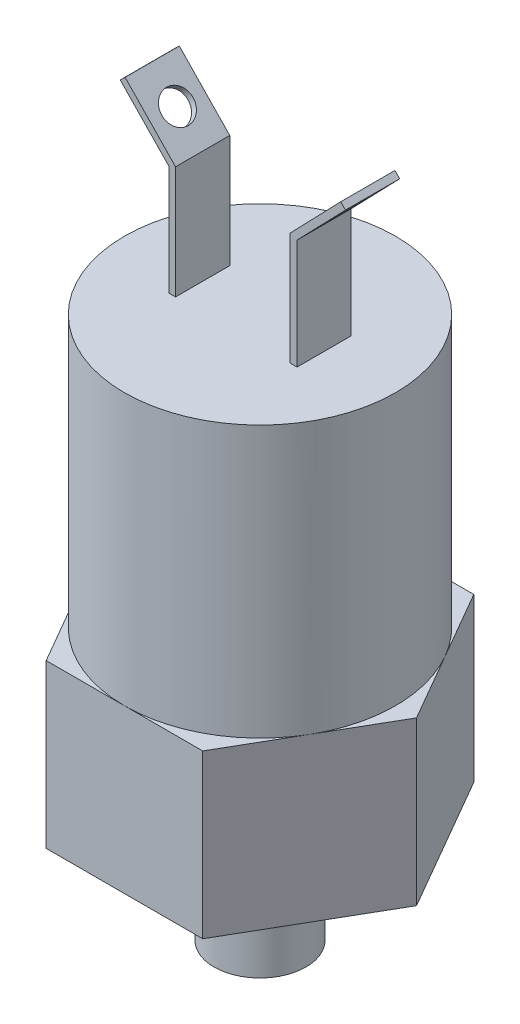
SolidWorks part; units mm, degrees
ref_plane "Front Plane" through (0, 0, 0) normal (0, 0, 1) x (1, 0, 0)
ref_plane "Top Plane" through (0, 0, 0) normal (0, 1, 0) x (1, 0, 0)
ref_plane "Right Plane" through (0, 0, 0) normal (1, 0, 0) x (0, 0, -1)
sketch "Sketch2" plane through (0, 0, 0) normal (0, 1, 0) x (1, 0, 0)
  line L0 (0, 0) -> (0, 12.7) construction
  line L1 (7.3323, 12.7) -> (-7.3323, 12.7)
  line L2 (-7.3323, 12.7) -> (-14.6647, 0)
  line L3 (-14.6647, 0) -> (-7.3323, -12.7)
  line L4 (-7.3323, -12.7) -> (7.3323, -12.7)
  line L5 (7.3323, -12.7) -> (14.6647, 0)
  line L6 (14.6647, 0) -> (7.3323, 12.7)
  circle A0 centre (0, 0) radius 12.7 construction
  dimension "D1" = 25.4
extrude "Boss-Extrude1" add sketch "Sketch2" along normal blind 15.24
sketch "Sketch3" plane through (0, 15.24, 0) normal (0, 1, 0) x (1, 0, 0)
  circle A0 centre (0, 0) radius 12.7
  dimension "D1" = 25.4
extrude "Boss-Extrude2" add sketch "Sketch3" along normal blind 25.4
sketch "Sketch4" plane through (0, 0, 0) normal (0, -1, 0) x (1, 0, 0)
  circle A0 centre (0, 0) radius 4.3053
  dimension "D1" = 8.6106
extrude "Boss-Extrude3" add sketch "Sketch4" along normal blind 10.16
cosmetic thread "Cosmetic Thread2" parameters "D2"=7.6106
sketch "Sketch5" plane through (0, 0, 0) normal (0, 0, 1) x (1, 0, 0)
  line L0 (5.6907, 40.64) -> (5.6907, 51.0752)
  line L1 (12.7, 40.64) -> (-12.7, 40.64) construction
  line L2 (5.6907, 51.0752) -> (10.3268, 55.88)
  dimension "D1" = 15.24
extrude "Extrude-Thin1" add sketch "Sketch5" along normal mid plane 5.08 thin thin type mid plane wall 0.635
sketch "Sketch6" plane through (-22.8028, 22.0022, 0) normal (-0.7196, 0.6944, 0) x (0, 0, 1)
  line L1 (2.54, 47.3833) -> (-2.54, 47.3833) construction
  line L2 (0, 43.9808) -> (0, 47.3833) construction
  line L3 (0, 43.9808) -> (-2.54, 43.9808) construction
  line L4 (-2.54, 40.5783) -> (-2.54, 47.3833) construction
  circle A0 centre (0, 43.9808) radius 1.4605
  dimension "D1" = 2.921
extrude "Cut-Extrude1" cut sketch "Sketch6" against normal up to next
mirror "Mirror1" about plane through (0, 0, 0) normal (1, 0, 0) of "Extrude-Thin1", "Cut-Extrude1"
